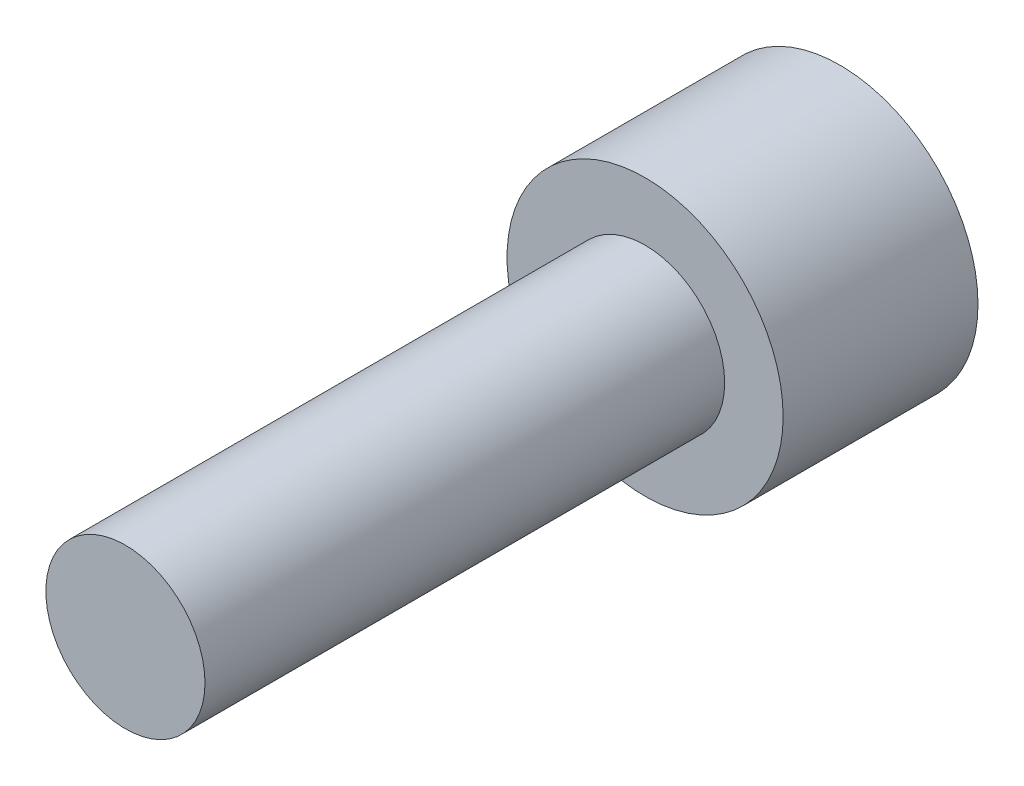
SolidWorks part; units mm, degrees
ref_plane "Front" through (0, 0, 0) normal (0, 0, 1) x (1, 0, 0)
ref_plane "Top" through (0, 0, 0) normal (0, 1, 0) x (1, 0, 0)
ref_plane "Right" through (0, 0, 0) normal (1, 0, 0) x (0, 0, -1)
sketch "Skizze1" plane through (0, 0, 0) normal (0, 0, 1) x (1, 0, 0)
  circle A0 centre (0, 0) radius 4.25
  dimension "D1" = 8.5
extrude "Aufsatz-Linear austragen1" add sketch "Skizze1" along normal blind 6
sketch "Skizze2" plane through (0, 0, 6) normal (0, 0, 1) x (1, 0, 0)
  circle A0 centre (0, 0) radius 2.45
  dimension "D1" = 4.9
extrude "Aufsatz-Linear austragen2" add sketch "Skizze2" along normal blind 16
